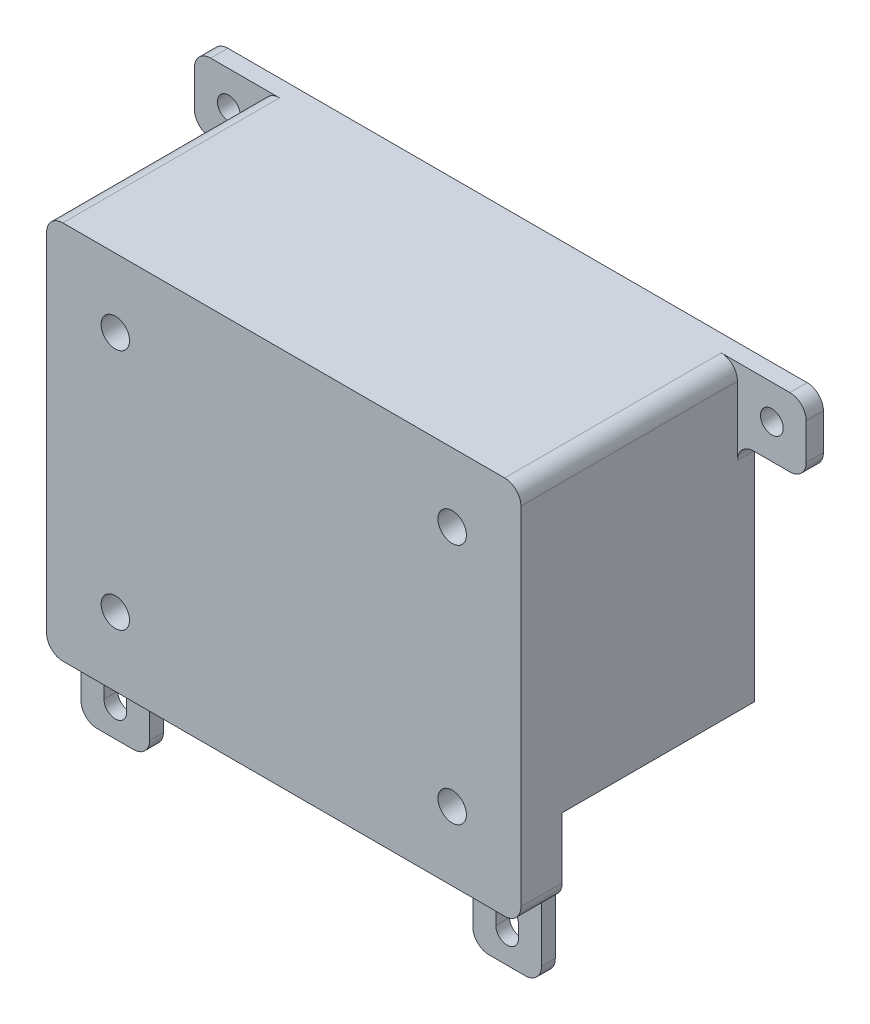
SolidWorks part; units mm, degrees
material "ABS"
ref_plane "X-Y Datum" through (0, 0, 0) normal (0, 0, 1) x (1, 0, 0)
ref_plane "X-Z Datum" through (0, 0, 0) normal (0, 1, 0) x (1, 0, 0)
ref_plane "Y-Z Datum" through (0, 0, 0) normal (1, 0, 0) x (0, 0, -1)
sketch "Sketch1" plane through (0, 0, 0) normal (0, 0, 1) x (1, 0, 0)
  line L0 (6.33, 73.27) -> (88.87, 73.27)
  line L1 (7.6, 72) -> (87.6, 72) construction
  line L2 (7.6, 72) -> (7.6, 9.5) construction
  line L3 (7.6, 9.5) -> (87.6, 9.5) construction
  line L4 (87.6, 72) -> (87.6, 9.5) construction
  line L5 (88.87, 73.27) -> (88.87, 8.23)
  line L6 (6.33, 8.23) -> (88.87, 8.23)
  line L7 (6.33, 73.27) -> (6.33, 8.23)
  circle A0 centre (12.6, 67) radius 2.125 construction
  circle A1 centre (82.6, 67) radius 2.125 construction
  circle A2 centre (82.6, 17) radius 2.125 construction
  circle A3 centre (12.6, 17) radius 2.125 construction
  dimension "D1" = 1.27
extrude "Boss-Extrude1" add sketch "Sketch1" along normal blind 43.18
shell "Shell1" thickness 2.54
sketch "Sketch6" plane through (3.79, 0, 0) normal (-1, 0, 0) x (0, 0, 1)
  line L24 (0, 81.9051) -> (38.1, 81.9051) construction
  line L25 (2.54, 59.03) -> (2.54, 73.27)
  line L26 (0, 59.03) -> (0, 3.15)
  line L27 (38.1, 3.15) -> (0, 3.15)
  line L28 (38.1, 19.9292) -> (38.1, 3.15)
  line L30 (2.54, 73.27) -> (0, 73.27)
  line L31 (0, 73.27) -> (0, 59.03)
  line L32 (20.32, 59.03) -> (20.32, 19.9292) construction
  line L34 (2.54, 19.9292) -> (38.1, 19.9292)
  line L35 (2.54, 59.03) -> (2.54, 19.9292)
  point P0 (0, 73.27)
extrude "Cut-Extrude2" cut sketch "Sketch6" against normal through all
sketch "Sketch7" plane through (0, 73.27, 0) normal (0, 1, 0) x (1, 0, 0)
  line L1 (3.79, -45.72) -> (91.41, -45.72)
  line L2 (3.79, -45.72) -> (3.79, -2.54)
  line L3 (3.79, -2.54) -> (91.41, -2.54)
  line L4 (91.41, -45.72) -> (91.41, -2.54)
extrude "Boss-Extrude2" add sketch "Sketch7" along normal blind 2.54
sketch "Sketch8" plane through (0, 0, 2.54) normal (0, 0, -1) x (-1, 0, 0)
  line L0 (-65.4056, 75.81) -> (-65.4056, 73.27)
  line L3 (-88.87, 73.27) -> (-6.33, 73.27) construction
  line L4 (-90.14, 19.9292) -> (-90.14, 74.54)
  line L5 (-91.41, 19.9292) -> (-88.87, 19.9292) construction
  line L6 (-5.06, 19.9292) -> (-5.06, 74.54)
  line L7 (-6.33, 19.9292) -> (-3.79, 19.9292) construction
  line L8 (-5.06, 74.54) -> (-90.14, 74.54)
  line L9 (-90.14, 19.9292) -> (-88.87, 19.9292)
  line L10 (-88.87, 19.9292) -> (-88.87, 73.27)
  line L11 (-88.87, 73.27) -> (-6.33, 73.27)
  line L12 (-6.33, 73.27) -> (-6.33, 19.9292)
  line L13 (-6.33, 19.9292) -> (-3.79, 19.9292) construction
  line L14 (-6.33, 19.9292) -> (-5.06, 19.9292)
  line M2 (-6.33, 73.27) -> (-6.33, 19.9292)
  line M3 (-6.33, 19.9292) -> (-3.79, 19.9292)
  line M7 (-91.41, 19.9292) -> (-88.87, 19.9292)
  line M8 (-88.87, 19.9292) -> (-88.87, 73.27)
  line M9 (-88.87, 73.27) -> (-6.33, 73.27)
extrude "Cut-Extrude3" cut sketch "Sketch8" against normal blind 2.54 contours L0 L8 L4 M7 M8 M9 | L6 L8 L0 M9 M2 M3
sketch "Sketch9" plane through (0, 0, 38.1) normal (0, 0, -1) x (-1, 0, 0)
  line L3 (-90.14, 19.9292) -> (-90.14, 6.96)
  line L4 (-90.14, 6.96) -> (-5.06, 6.96)
  line L5 (-5.06, 6.96) -> (-5.06, 19.9292)
  line L6 (-6.33, 19.9292) -> (-3.79, 19.9292) construction
  line L7 (-5.06, 19.9292) -> (-6.33, 19.9292)
  line L8 (-6.33, 19.9292) -> (-6.33, 8.23)
  line L9 (-6.33, 8.23) -> (-88.87, 8.23)
  line L10 (-88.87, 8.23) -> (-88.87, 19.9292)
  line L11 (-88.87, 19.9292) -> (-90.14, 19.9292)
extrude "Cut-Extrude4" cut sketch "Sketch9" against normal blind 2.54
sketch "Sketch10" plane through (0, 19.9292, 0) normal (0, -1, 0) x (1, 0, 0)
  line L1 (5.06, 5.08) -> (6.33, 5.08)
  line L2 (5.06, 5.08) -> (5.06, 40.64)
  line L3 (5.06, 40.64) -> (6.33, 40.64)
  line L4 (6.33, 5.08) -> (6.33, 40.64)
  line L5 (90.14, 5.08) -> (88.87, 5.08)
  line L6 (90.14, 5.08) -> (90.14, 40.64)
  line L7 (90.14, 40.64) -> (88.87, 40.64)
  line L8 (88.87, 5.08) -> (88.87, 40.64)
extrude "Cut-Extrude5" cut sketch "Sketch10" against normal blind 2.54
sketch "Sketch11" plane through (0, 5.69, 0) normal (0, -1, 0) x (1, 0, 0)
  line L0 (90.14, 5.08) -> (90.14, 40.64) construction
  line L1 (5.06, 38.1) -> (17.76, 38.1)
  line L2 (5.06, 38.1) -> (5.06, 40.64)
  line L3 (5.06, 40.64) -> (17.76, 40.64)
  line L4 (17.76, 38.1) -> (17.76, 40.64)
  line L5 (90.14, 38.1) -> (77.44, 38.1)
  line L6 (90.14, 38.1) -> (90.14, 40.64)
  line L7 (90.14, 40.64) -> (77.44, 40.64)
  line L8 (77.44, 38.1) -> (77.44, 40.64)
  line L9 (91.41, 38.1) -> (90.14, 38.1) construction
extrude "Boss-Extrude3" add sketch "Sketch11" along normal blind 12.7
sketch "Sketch12" plane through (0, 0, 40.64) normal (0, 0, 1) x (1, 0, 0)
  line L0 (11.41, -0.6201) -> (11.41, 0.61) construction
  line L3 (11.41, -0.6201) -> (11.41, -1.6835) construction
  line L4 (9.31, 0.61) -> (9.31, -1.6835)
  line L5 (13.51, 0.61) -> (13.51, -1.6835)
  line L6 (47.6, 5.69) -> (47.6, 25.4131) construction
  line L7 (3.79, 5.69) -> (91.41, 5.69) construction
  line L8 (83.79, -0.6201) -> (83.79, -1.6835) construction
  line L9 (83.79, -0.6201) -> (83.79, 0.61) construction
  line L10 (81.69, 0.61) -> (81.69, -1.6835)
  line L11 (85.89, 0.61) -> (85.89, -1.6835)
  arc A0 (13.51, 0.61) -> (9.31, 0.61) centre (11.41, 0.61) ccw
  arc A1 (9.31, -1.6835) -> (13.51, -1.6835) centre (11.41, -1.6835) ccw
  arc A2 (85.89, -1.6835) -> (81.69, -1.6835) centre (83.79, -1.6835) cw
  arc A3 (81.69, 0.61) -> (85.89, 0.61) centre (83.79, 0.61) cw
  point P6 (11.41, -0.6201)
  point P19 (83.79, -0.6201)
ref_plane "Plane1" through (47.6, 0, 0) normal (-1, 0, 0) x (0, 0, 1)
extrude "Cut-Extrude7" cut sketch "Sketch12" against normal through all
sketch "Sketch13" plane through (0, 0, 2.54) normal (0, 0, -1) x (-1, 0, 0)
  line L1 (-91.41, 75.81) -> (-104.11, 75.81)
  line L2 (-91.41, 75.81) -> (-91.41, 63.11)
  line L3 (-91.41, 63.11) -> (-104.11, 63.11)
  line L4 (-104.11, 75.81) -> (-104.11, 63.11)
  line L5 (-3.79, 75.81) -> (8.91, 75.81)
  line L6 (-3.79, 75.81) -> (-3.79, 63.11)
  line L7 (-3.79, 63.11) -> (8.91, 63.11)
  line L8 (8.91, 75.81) -> (8.91, 63.11)
  circle A0 centre (-97.76, 69.46) radius 2.1
  circle A1 centre (2.56, 69.46) radius 2.1
extrude "Boss-Extrude4" add sketch "Sketch13" against normal blind 3.175
fillet "Fillet2" radius 3 16 edges at (77.44, 5.69, 39.37) (77.44, -7.01, 39.37) (90.14, -7.01, 39.37) (17.76, -7.01, 39.37) (5.06, -7.01, 39.37) (17.76, 5.69, 39.37) (3.79, 63.11, 4.1275) (-8.91, 63.11, 4.1275) (-8.91, 75.81, 4.1275) (104.11, 63.11, 4.1275) (91.41, 63.11, 4.1275) (104.11, 75.81, 4.1275) (91.41, 75.81, 25.7175) (3.79, 75.81, 25.7175) (3.79, 5.69, 41.91) (91.41, 5.69, 41.91)
sketch "Sketch14" plane through (0, 0, 45.72) normal (0, 0, 1) x (1, 0, 0)
  line L0 (3.79, 75.81) -> (16.49, 75.81) construction
  line L1 (-5.91, 75.81) -> (6.79, 75.81) construction
  line L2 (6.79, 75.81) -> (88.41, 75.81) construction
  line L3 (16.49, 75.81) -> (16.49, 63.11) construction
  line L4 (3.79, 40.75) -> (-3.6453, 40.75) construction
  line L6 (47.6, 23.749) -> (47.6, -23.749) construction
  circle A0 centre (16.49, 63.11) radius 6.35
  circle A1 centre (16.49, 18.39) radius 6.35
  circle A2 centre (78.71, 18.39) radius 6.35
  circle A3 centre (78.71, 63.11) radius 6.35
extrude "Boss-Extrude5" add sketch "Sketch14" against normal blind 5
sketch "Sketch15" plane through (0, 0, 45.72) normal (0, 0, 1) x (1, 0, 0)
  circle A0 centre (16.49, 63.11) radius 2.625
  circle A1 centre (78.71, 63.11) radius 2.625
  circle A2 centre (16.49, 18.39) radius 2.625
  circle A3 centre (78.71, 18.39) radius 2.625
extrude "Cut-Extrude8" cut sketch "Sketch15" against normal up to surface (5 mm away) up to face at (85.06, 18.39, 40.72)
sketch "Sketch17" plane through (0, 0, 45.72) normal (0, 0, 1) x (1, 0, 0)
  line L0 (6.79, 75.81) -> (88.41, 75.81) construction
  line L1 (3.79, 5.69) -> (29.19, 5.69)
  line L2 (3.79, 5.69) -> (3.79, 75.81)
  line L3 (3.79, 75.81) -> (29.19, 75.81)
  line L4 (29.19, 5.69) -> (29.19, 66.7397)
  line L5 (47.6, 23.749) -> (47.6, -23.749) construction
  line L6 (91.41, 75.81) -> (66.01, 75.81)
  line L7 (66.01, 5.69) -> (66.01, 66.7397)
  line L8 (91.41, 5.69) -> (66.01, 5.69)
  line L9 (91.41, 5.69) -> (91.41, 75.81)
  line L11 (29.19, 75.81) -> (66.01, 75.81)
  line L13 (29.19, 66.7397) -> (66.01, 66.7397)
  circle A0 centre (16.49, 63.11) radius 1.0911
  circle A1 centre (16.49, 18.39) radius 1.2652
  circle A2 centre (78.71, 63.11) radius 1.7171
  circle A3 centre (78.71, 18.39) radius 1.4554
